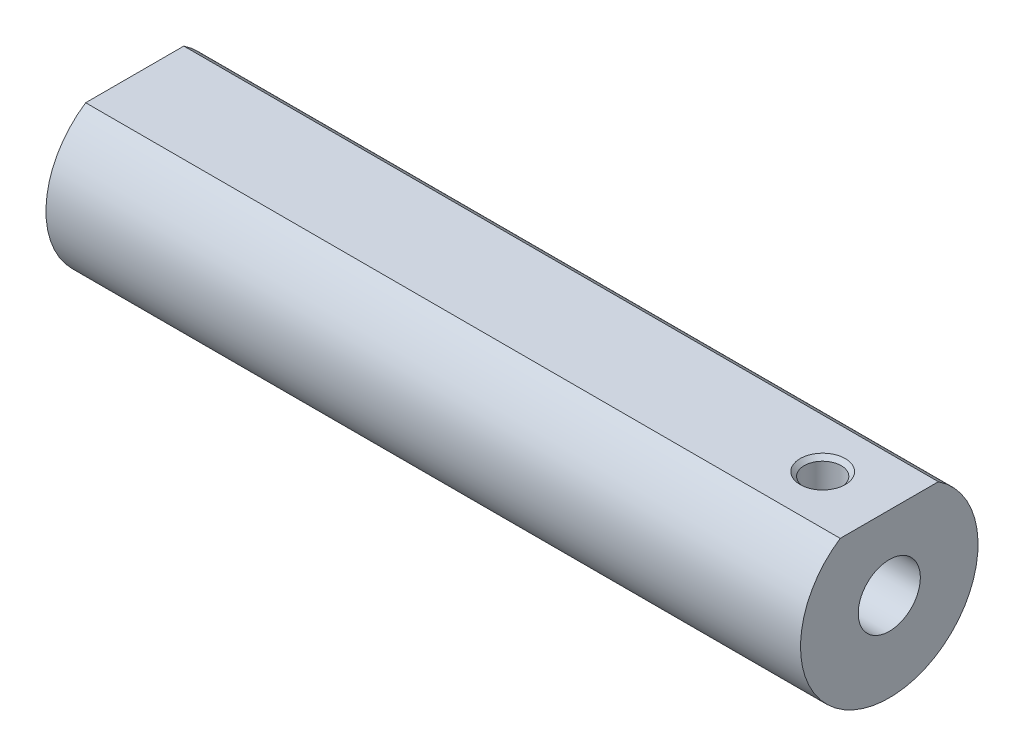
SolidWorks part; units mm, degrees
ref_plane "Front Plane" through (0, 0, 0) normal (0, 0, 1) x (1, 0, 0)
ref_plane "Top Plane" through (0, 0, 0) normal (0, 1, 0) x (1, 0, 0)
ref_plane "Right Plane" through (0, 0, 0) normal (1, 0, 0) x (0, 0, -1)
sketch "Sketch1" plane through (0, 0, 0) normal (1, 0, 0) x (0, 0, -1)
  circle A0 centre (0, 0) radius 6
  dimension "D1" = 12
extrude "Boss-Extrude1" add sketch "Sketch1" along normal blind 51
sketch "Sketch2" plane through (51, 0, 0) normal (1, 0, 0) x (0, 0, -1)
  line L0 (-3.3166, 5) -> (3.3166, 5)
  circle A0 centre (0, 0) radius 2.1
  circle A1 centre (0, 0) radius 6 construction
  arc A2 (-3.3166, 5) -> (3.3166, 5) centre (0, 0) cw
  dimension "D1" = 4.2
  dimension "D2" = 5
extrude "Cut-Extrude1" cut sketch "Sketch2" against normal blind 12
sketch "Sketch5" plane through (0, 5, 0) normal (0, 1, 0) x (1, 0, 0)
  line L0 (51, 0) -> (39, 0) construction
  line L1 (51, -3.3166) -> (51, 3.3166) construction
  line L2 (39, -3.3166) -> (39, 3.3166) construction
  point P6 (46.5, 0)
  dimension "D1" = 4.5
hole_wizard "M3 Tapped Hole1" positions "3DSketch2" profile "Sketch6" tap size "M3" standard "ISO"
sketch3d "3DSketch2"
  point P0 (46.5, 5, 0)
cosmetic thread "Hole Thread1" parameters "D1"=3.3125, "D2"=3
sketch "Sketch6" plane through (46.5, 5, 0) normal (1, 0, 0) x (0, 0, 1)
  line L0 (0, 0) -> (0, 6.7511)
  line L1 (0, 6.7511) -> (1.25, 6)
  line L2 (1.25, 6) -> (1.25, 0.275)
  line L3 (1.25, 0.275) -> (1.525, 0)
  line L5 (1.525, 0) -> (0, 0)
  line L6 (-1.25, 0.275) -> (-1.525, 0) construction
  line L10 (0, 6.7511) -> (-1.25, 6) construction
  line L11 (0, -6.35) -> (0, 107.95) construction
  dimension "Tap Drill Dia." = 2.5
  dimension "Tap Drill Depth" = 6
  dimension "Near C'Sink Dia." = 3.05
  dimension "Near C'Sink Angle" = 90
  dimension "Drill Angle" = 118
sketch "Sketch7" plane through (39, 0, 0) normal (1, 0, 0) x (0, 0, -1)
  line L1 (-3.3166, 5) -> (3.3166, 5)
  line L2 (-3.3166, 5) -> (3.3166, 5)
  arc A1 (3.3166, 5) -> (-3.3166, 5) centre (0, 0) ccw
  arc A2 (3.3166, 5) -> (-3.3166, 5) centre (0, 0) ccw
  dimension "D1" = 0
extrude "Cut-Extrude2" cut sketch "Sketch7" against normal up to next
